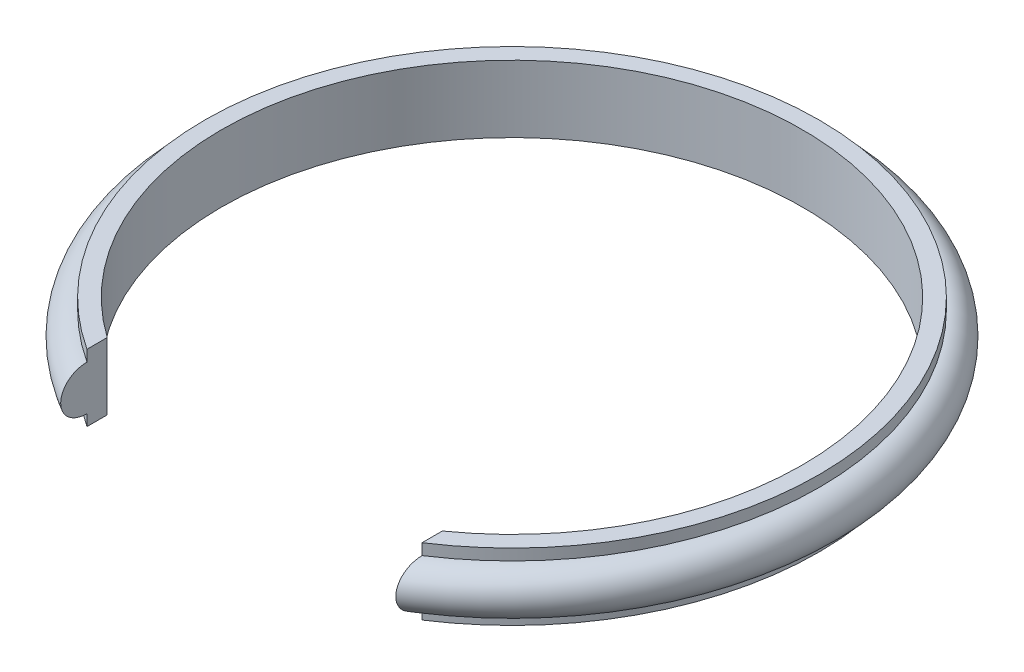
SolidWorks part; units mm, degrees
ref_plane "Front Plane" through (0, 0, 0) normal (0, 0, 1) x (1, 0, 0)
ref_plane "Top Plane" through (0, 0, 0) normal (0, 1, 0) x (1, 0, 0)
ref_plane "Right Plane" through (0, 0, 0) normal (1, 0, 0) x (0, 0, -1)
sketch "Sketch1" plane through (0, 0, 0) normal (0, 0, 1) x (1, 0, 0)
  line L0 (0, 27.5802) -> (0, -27.1403) construction
  line L1 (-26, -3) -> (-26, 3)
  line L2 (-26, 3) -> (-27.5, 3)
  line L3 (-27.5, 3) -> (-27.5, 2)
  line L4 (-27.5, -2) -> (-27.5, -3)
  line L5 (-27.5, -3) -> (-26, -3)
  arc A0 (-27.5, 2) -> (-27.5, -2) centre (-27.5, 0) ccw
  point P6 (-26, 0)
  point P10 (0, 0)
  dimension "D1" = 4
  dimension "D2" = 1
  dimension "D3" = 52
  dimension "D4" = 55
revolve "Revolve1" add sketch "Sketch1" angle 360 about L0
sketch "Sketch3" plane through (0, 0, 0) normal (0, 0, 1) x (1, 0, 0)
  line L0 (26, 3) -> (-26, 3) construction
  line L1 (-15, -3) -> (15, -3)
  line L2 (-15, -3) -> (-15, 3)
  line L3 (-15, 3) -> (15, 3)
  line L4 (15, -3) -> (15, 3)
  line L5 (-15, -3) -> (15, 3) construction
  line L6 (-15, 3) -> (15, -3) construction
  point P0 (0, 0)
  dimension "D1" = 30
extrude "Cut-Extrude1" cut sketch "Sketch3" along normal through all
